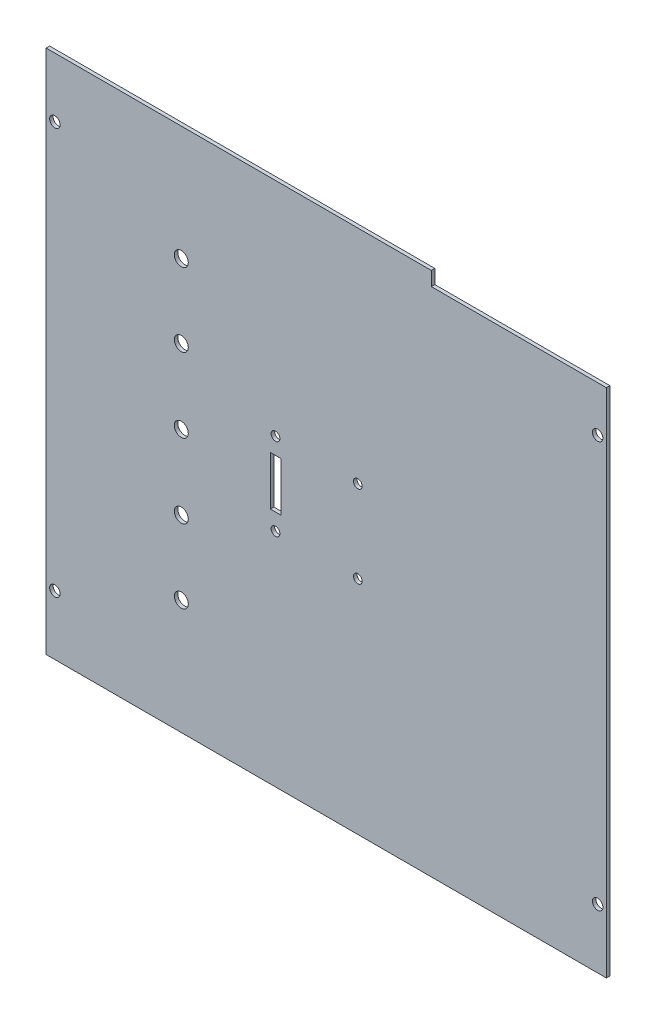
SolidWorks part; units mm, degrees
ref_plane "Front Plane" through (0, 0, 0) normal (0, 0, 1) x (1, 0, 0)
ref_plane "Top Plane" through (0, 0, 0) normal (0, 1, 0) x (1, 0, 0)
ref_plane "Right Plane" through (0, 0, 0) normal (1, 0, 0) x (0, 0, -1)
sketch "Sketch1" plane through (0, 0, 0) normal (0, 0, 1) x (1, 0, 0)
  line L1 (-80, 75) -> (80, 75)
  line L2 (-80, 75) -> (-80, -75)
  line L3 (-80, -75) -> (80, -75)
  line L4 (80, 75) -> (80, -75)
  line L5 (-80, 75) -> (80, -75) construction
  line L6 (-80, -75) -> (80, 75) construction
  point P0 (0, 0)
  dimension "D1" = 160
  dimension "D2" = 150
extrude "Boss-Extrude1" add sketch "Sketch1" along normal blind 1
sketch "Sketch3" plane through (0, 0, 1) normal (0, 0, 1) x (1, 0, 0)
  line L0 (-80, 0) -> (80, 0) construction
  line L1 (-80, 75) -> (-80, -75) construction
  line L2 (80, -75) -> (80, 75) construction
  line L4 (80, 75) -> (30, 75)
  line L5 (80, 75) -> (80, 71)
  line L6 (80, 71) -> (30, 71)
  line L7 (30, 75) -> (30, 71)
  line L8 (-15.9839, -7) -> (-12.9839, -7)
  line L9 (-15.9839, -7) -> (-15.9839, 7)
  line L10 (-15.9839, 7) -> (-12.9839, 7)
  line L11 (-12.9839, -7) -> (-12.9839, 7)
  line L12 (-15.9839, -7) -> (-12.9839, 7) construction
  line L13 (-15.9839, 7) -> (-12.9839, -7) construction
  circle A0 centre (-77.5, -58) radius 1.5
  circle A1 centre (77.5, -58) radius 1.5
  circle A2 centre (77.5, 58) radius 1.5
  circle A3 centre (-77.5, 58) radius 1.5
  circle A4 centre (-14.4839, -11.75) radius 1.25
  circle A5 centre (9.0161, -11.75) radius 1.25
  circle A6 centre (9.0161, 11.75) radius 1.25
  circle A7 centre (-14.4839, 11.75) radius 1.25
  circle A8 centre (-41.4015, 0) radius 2
  circle A9 centre (-41.4015, -21.2157) radius 2
  circle A10 centre (-41.4015, 21.2157) radius 2
  circle A11 centre (-41.4015, -42.2189) radius 2
  circle A12 centre (-41.4015, 42.2189) radius 2
  point P33 (-14.4839, 0)
  dimension "D1" = 155
  dimension "D7" = 23.5
  dimension "D9" = 21.2157
  dimension "D8" = 4
  dimension "D2" = 14
  dimension "D3" = 3
  dimension "D4" = 4
  dimension "D5" = 50
  dimension "D6" = 2.5
extrude "Cut-Extrude1" cut sketch "Sketch3" against normal blind 10
